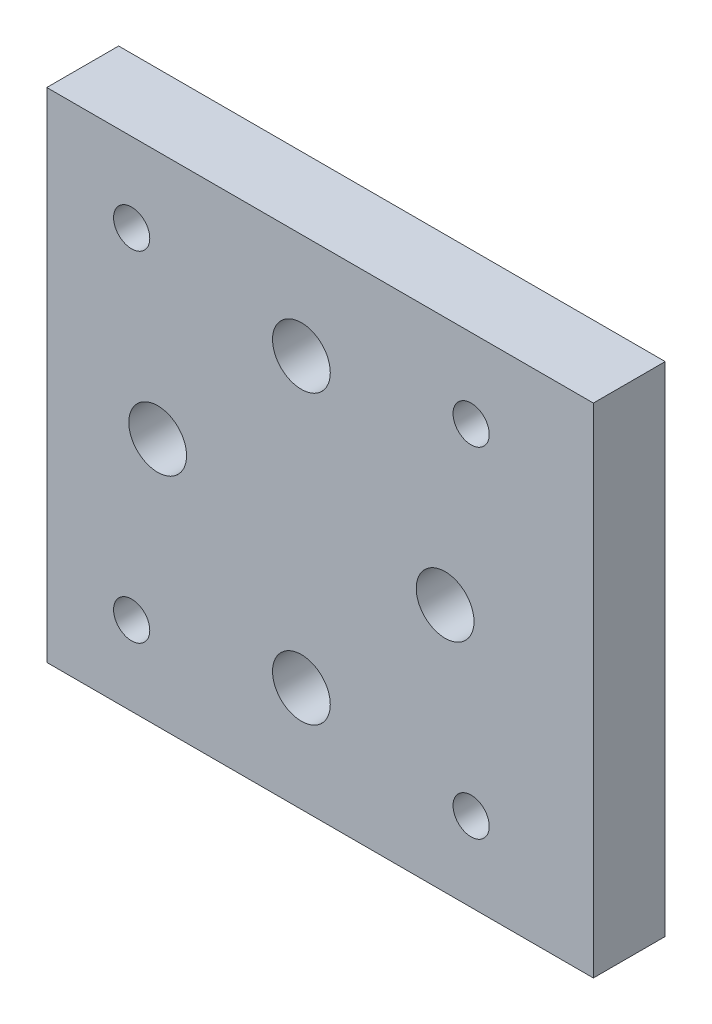
SolidWorks part; units mm, degrees
ref_plane "Front Plane" through (0, 0, 0) normal (0, 0, 1) x (1, 0, 0)
ref_plane "Top Plane" through (0, 0, 0) normal (0, 1, 0) x (1, 0, 0)
ref_plane "Right Plane" through (0, 0, 0) normal (1, 0, 0) x (0, 0, -1)
sketch "Sketch1" plane through (0, 0, 0) normal (0, 0, 1) x (1, 0, 0)
  line L0 (22.5, -9.3) -> (22.5, -34.7) construction
  line L1 (0, 0) -> (48.3, 0)
  line L2 (0, 0) -> (0, -44)
  line L3 (0, -44) -> (48.3, -44)
  line L4 (48.3, 0) -> (48.3, -44)
  line L5 (9.8, -22) -> (35.2, -22) construction
  circle A0 centre (7.5, -37) radius 1.6
  circle A16 centre (22.5, -9.3) radius 2.5527
  circle A17 centre (35.2, -22) radius 2.5527
  circle A18 centre (9.8, -22) radius 2.5527
  circle A19 centre (22.5, -34.7) radius 2.5527
  circle A20 centre (37.5, -37) radius 1.6
  circle A21 centre (37.5, -7) radius 1.6
  circle A22 centre (7.5, -7) radius 1.6
  point P12 (48.3, -22)
  point P47 (22.5, -22)
  dimension "D3" = 3.2
  dimension "D10" = 5.1054
  dimension "D1" = 48.3
  dimension "D2" = 44
  dimension "D4" = 7.5
  dimension "D5" = 7
  dimension "D11" = 25.4
  dimension "D8" = 30
  dimension "D9" = 30
  dimension "D12" = 22.5
  dimension "D6" = 2
  dimension "D7" = 2
extrude "Boss-Extrude1" add sketch "Sketch1" along normal blind 6.35
hole_wizard "1/4-20 Tapped Hole1" positions "3DSketch1" profile "Sketch2" tap size "1/4-20" standard "ANSI Inch" end condition through all
sketch3d "3DSketch1"
  circle A0 centre (22.5, -9.3, 6.35) radius 2.5527 construction
  circle A1 centre (9.8, -22, 6.35) radius 2.5527 construction
  circle A2 centre (22.5, -34.7, 6.35) radius 2.5527 construction
  circle A3 centre (35.2, -22, 6.35) radius 2.5527 construction
  point P0 (22.5, -9.3, 6.35)
  point P2 (35.2, -22, 6.35)
  point P4 (9.8, -22, 6.35)
  point P6 (22.5, -34.7, 6.35)
  point P9 (0, 0, 0)
  point P10 (0, 0, 0)
  point P13 (22.5, -9.3, 8.9027)
  point P14 (0, 0, 0)
  point P15 (0, 0, 0)
  point P16 (0, 0, 0)
  point P17 (0, 0, 0)
  point P20 (9.8, -22, 8.9027)
  point P21 (0, 0, 0)
  point P24 (22.5, -34.7, 8.9027)
  point P25 (0, 0, 0)
  point P28 (35.2, -22, 8.9027)
sketch "Sketch2" plane through (22.5, -9.3, 6.35) normal (1, 0, 0) x (0, -1, 0)
  line L0 (0, 0) -> (0, 6.35)
  line L1 (0, 6.35) -> (2.5527, 6.35)
  line L2 (2.5527, 6.35) -> (2.5527, 0)
  line L5 (2.5527, 0) -> (0, 0)
  line L11 (0, -6.35) -> (0, 107.95) construction
  dimension "Thru Tap Drill Dia." = 5.1054
  dimension "Thru Tap Drill Depth" = 6.35
cosmetic thread "Hole Thread1" parameters "D2"=6.35
cosmetic thread "Hole Thread2" parameters "D2"=6.35
cosmetic thread "Hole Thread3" parameters "D2"=6.35
cosmetic thread "Hole Thread4" parameters "D2"=6.35
equation "\"D4@Sketch1\"=(\"D1@Sketch1\"-\"D9@Sketch1\")/2-1.65"
